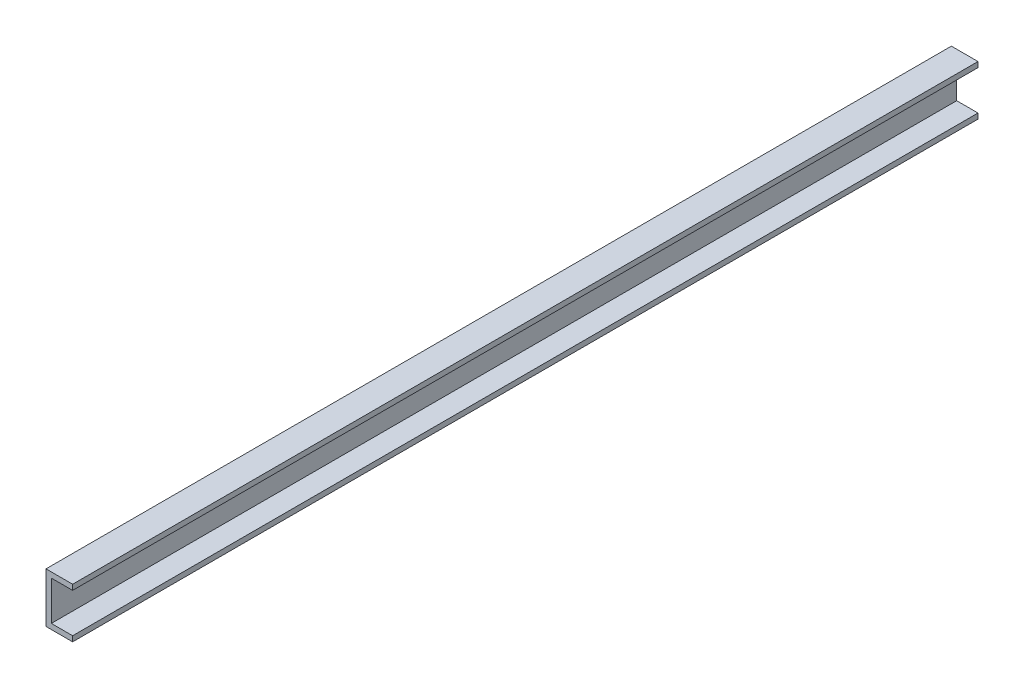
SolidWorks part; units mm, degrees
ref_plane "Front Plane" through (0, 0, 0) normal (0, 0, 1) x (1, 0, 0)
ref_plane "Top Plane" through (0, 0, 0) normal (0, 1, 0) x (1, 0, 0)
ref_plane "Right Plane" through (0, 0, 0) normal (1, 0, 0) x (0, 0, -1)
sketch "Sketch1" plane through (0, 0, 0) normal (0, 0, 1) x (1, 0, 0)
  line L0 (0, 0) -> (0, 75)
  line L1 (0, 75) -> (40, 75)
  line L2 (40, 75) -> (40, 67)
  line L3 (40, 67) -> (8, 67)
  line L4 (8, 67) -> (8, 8)
  line L5 (8, 8) -> (40, 8)
  line L6 (40, 8) -> (40, 0)
  line L7 (40, 0) -> (0, 0)
  dimension "D1" = 75
  dimension "D2" = 40
  dimension "D3" = 8
  dimension "D4" = 8
  dimension "D5" = 8
extrude "Boss-Extrude1" add sketch "Sketch1" along normal blind 1360
